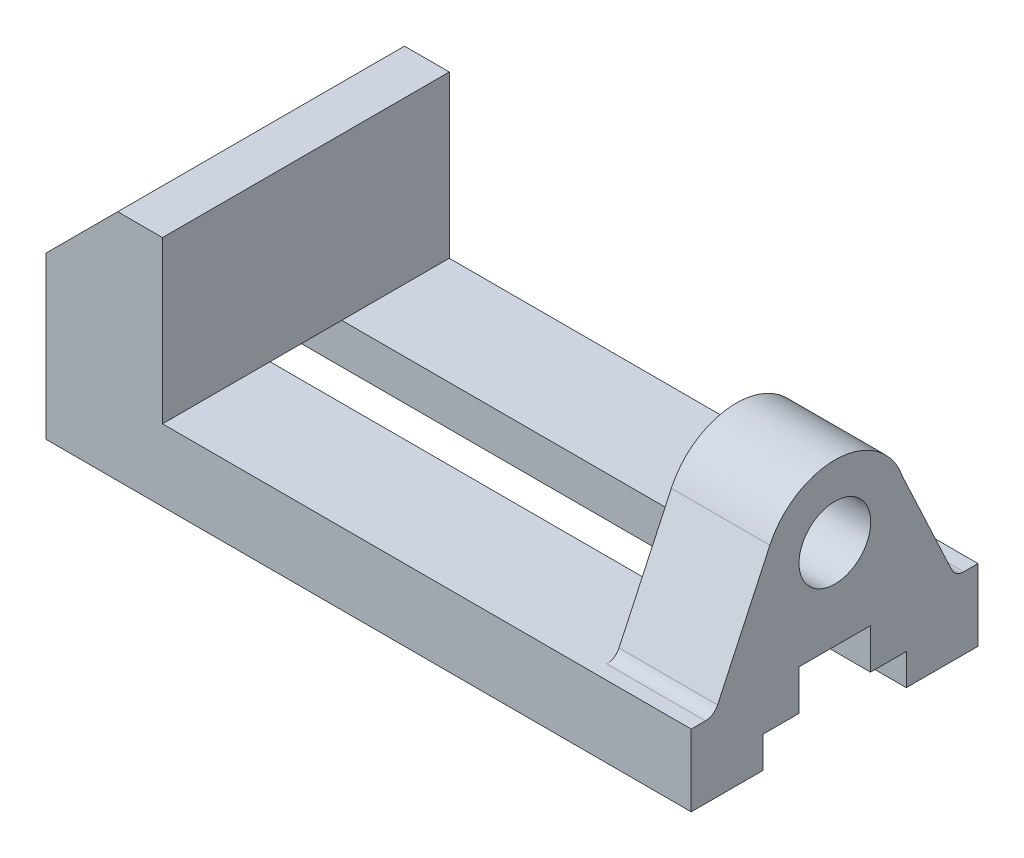
SolidWorks part; units mm, degrees
ref_plane "Front Plane" through (0, 0, 0) normal (0, 0, 1) x (1, 0, 0)
ref_plane "Top Plane" through (0, 0, 0) normal (0, 1, 0) x (1, 0, 0)
ref_plane "Right Plane" through (0, 0, 0) normal (1, 0, 0) x (0, 0, -1)
sketch "Sketch3" plane through (0, 0, 0) normal (0, 0, 1) x (1, 0, 0)
  line L0 (0, 0) -> (0, 36)
  line L1 (0, 36) -> (16, 52)
  line L2 (16, 52) -> (26, 52)
  line L3 (26, 52) -> (26, 16)
  line L4 (26, 16) -> (144, 16)
  line L5 (144, 16) -> (144, 0)
  line L6 (144, 0) -> (0, 0)
  dimension "D1" = 16
  dimension "D2" = 144
  dimension "D3" = 10
  dimension "D4" = 16
  dimension "D5" = 16
  dimension "D6" = 36
extrude "Boss-Extrude1" add sketch "Sketch3" along normal mid plane 64
sketch "Sketch4" plane through (144, 0, 0) normal (1, 0, 0) x (0, 0, -1)
  line L0 (0, 0) -> (0, 61.3686) construction
  line L1 (-26.9271, 16) -> (-14.4479, 42.7619)
  line L2 (15.2072, 41.1335) -> (26.9271, 16)
  line L3 (26.9271, 16) -> (-26.9271, 16)
  line L4 (-32, 52) -> (32, 52) construction
  line L5 (-32, 16) -> (32, 16) construction
  arc A0 (-14.4479, 42.7619) -> (15.2072, 41.1335) centre (0.0531, 36) cw
  point P7 (0, 0)
  dimension "D2" = 16
  dimension "D1" = 50
sketch "Sketch9" plane through (26, 0, 0) normal (1, 0, 0) x (0, 0, -1)
extrude "Boss-Extrude7" add sketch "Sketch4" against normal blind 22 contours L3 L1 A0 L2
sketch "Sketch10" plane through (144, 0, 0) normal (1, 0, 0) x (0, 0, -1)
  circle A1 centre (0.0531, 36) radius 8
  dimension "D1" = 16
extrude "Cut-Extrude1" cut sketch "Sketch10" against normal blind 22
fillet "Fillet1" radius 3 1 edges at (133, 16, 26.9271)
fillet "Fillet2" radius 3 1 edges at (133, 16, -26.9271)
sketch "Sketch11" plane through (144, 0, 0) normal (1, 0, 0) x (0, 0, -1)
  line L0 (0, 0) -> (0, 33.559) construction
  line L1 (-16, -7.5931) -> (-16, 7)
  line L2 (-16, 7) -> (-8, 7)
  line L3 (-8, 7) -> (-8, 16)
  line L4 (-8, 16) -> (8, 16)
  line L5 (8, 16) -> (8, 7)
  line L6 (8, 7) -> (16, 7)
  line L7 (16, 7) -> (16, -7.5931)
  line L8 (16, -7.5931) -> (-16, -7.5931)
  line L9 (-32, 0) -> (32, 0) construction
  dimension "D1" = 16
  dimension "D2" = 7
  dimension "D3" = 16
  dimension "D4" = 32
extrude "Cut-Extrude2" cut sketch "Sketch11" against normal through all
hole_wizard "Ø1.0mm Dowel Hole1" positions "3DSketch2" profile "Sketch13" hole size "Ø1.0" standard "ANSI Metric"
sketch3d "3DSketch2"
  line L0 (144, 0, 32) -> (144, 0, 16) construction
  line L1 (0, 0, 32) -> (144, 0, 32) construction
  point P0 (106, 0, 22)
  dimension "D1" = 38
  dimension "D2" = 10
sketch "Sketch13" plane through (106, 0, 22) normal (1, 0, 0) x (0, 0, -1)
  line L0 (0, 0) -> (0, 11.7321)
  line L1 (0, 11.7321) -> (3, 10)
  line L2 (3, 10) -> (3, 0)
  line L5 (3, 0) -> (0, 0)
  line L10 (0, 11.7321) -> (-3, 10) construction
  line L11 (0, -6.35) -> (0, 107.95) construction
  dimension "Hole Dia." = 6
  dimension "Hole Depth" = 10
  dimension "Drill Angle" = 120
pattern_linear "LPattern1" count 2 spacing 70 along (-1, 0, 0) count 2 spacing 44 along (0, 0, -1) of "Ø1.0mm Dowel Hole1"
